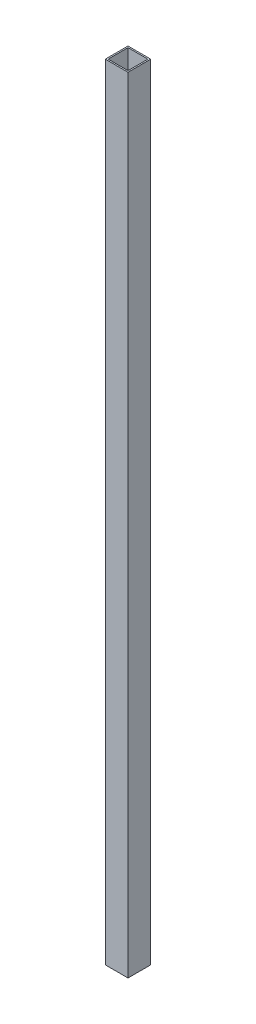
SolidWorks part; units mm, degrees
ref_plane "Front Plane" through (0, 0, 0) normal (0, 0, 1) x (1, 0, 0)
ref_plane "Top Plane" through (0, 0, 0) normal (0, 1, 0) x (1, 0, 0)
ref_plane "Right Plane" through (0, 0, 0) normal (1, 0, 0) x (0, 0, -1)
sketch "Sketch1" plane through (0, 0, 0) normal (0, 1, 0) x (1, 0, 0)
  line L1 (12.7, 12.7) -> (-12.7, 12.7)
  line L2 (12.7, 12.7) -> (12.7, -12.7)
  line L3 (12.7, -12.7) -> (-12.7, -12.7)
  line L4 (-12.7, 12.7) -> (-12.7, -12.7)
  line L5 (12.7, 12.7) -> (-12.7, -12.7) construction
  line L6 (12.7, -12.7) -> (-12.7, 12.7) construction
  line L7 (11.1125, 11.1125) -> (-11.1125, 11.1125)
  line L8 (11.1125, 11.1125) -> (11.1125, -11.1125)
  line L9 (11.1125, -11.1125) -> (-11.1125, -11.1125)
  line L10 (-11.1125, 11.1125) -> (-11.1125, -11.1125)
  line L11 (11.1125, 11.1125) -> (-11.1125, -11.1125) construction
  line L12 (11.1125, -11.1125) -> (-11.1125, 11.1125) construction
  point P0 (0, 0)
  point P6 (0, 0)
  dimension "D1" = 25.4
  dimension "D2" = 25.4
  dimension "D3" = 1.5875
  dimension "D4" = 1.5875
extrude "Boss-Extrude1" add sketch "Sketch1" along normal blind 876.3
